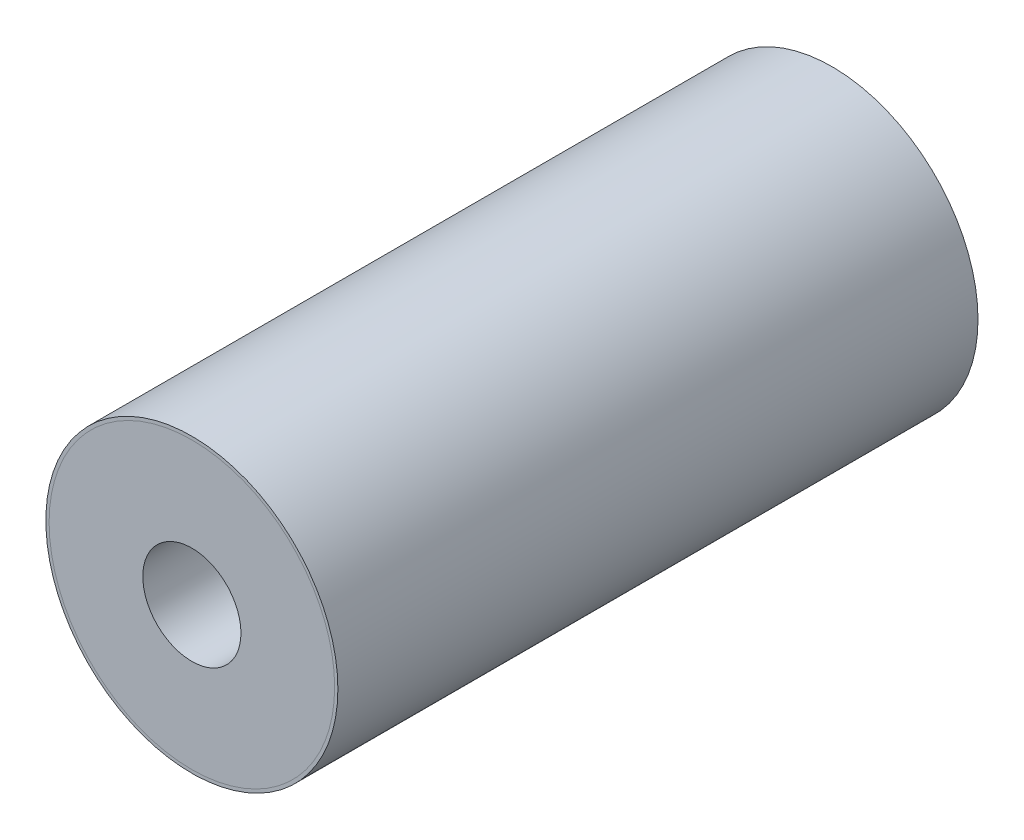
SolidWorks part; units mm, degrees
other "03170L"
other "8125RC"
material "APCP"
ref_plane "Front Plane" through (0, 0, 0) normal (0, 0, 1) x (1, 0, 0)
ref_plane "Top Plane" through (0, 0, 0) normal (0, 1, 0) x (1, 0, 0)
ref_plane "Right Plane" through (0, 0, 0) normal (1, 0, 0) x (0, 0, -1)
sketch "Sketch1" plane through (0, 0, 0) normal (0, 0, 1) x (1, 0, 0)
  circle A0 centre (0, 0) radius 16.5481
  circle A1 centre (0, 0) radius 16.1798
  dimension "D1" = 33.0962
  dimension "D2" = 32.3596
extrude "Boss-Extrude1" add sketch "Sketch1" along normal blind 72.5424
sketch "Sketch2" plane through (0, 0, 0) normal (0, 0, 1) x (1, 0, 0)
  circle A0 centre (0, 0) radius 16.1798
  circle A1 centre (0, 0) radius 16.1798 construction
extrude "Boss-Extrude2" add sketch "Sketch2" along normal up to surface (72.5424 mm away) separate body up to face at (16.5481, 0, 72.5424)
sketch "Sketch3" plane through (0, 0, 72.5424) normal (0, 0, 1) x (1, 0, 0)
  point P0 (0, 0)
hole_wizard "7/16 (0.438) Diameter Hole1" positions "Sketch3" profile "Sketch4" hole size "7/16" standard "ANSI Inch" end condition through all
sketch "Sketch4" plane through (0, 0, 72.5424) normal (1, 0, 0) x (0, -1, 0)
  line L0 (0, 0) -> (0, 72.5424)
  line L1 (0, 72.5424) -> (5.5626, 72.5424)
  line L2 (5.5626, 72.5424) -> (5.5626, 0)
  line L5 (5.5626, 0) -> (0, 0)
  line L11 (0, -6.35) -> (0, 107.95) construction
  dimension "Thru Hole Dia." = 11.1252
  dimension "Thru Hole Depth" = 72.5424
